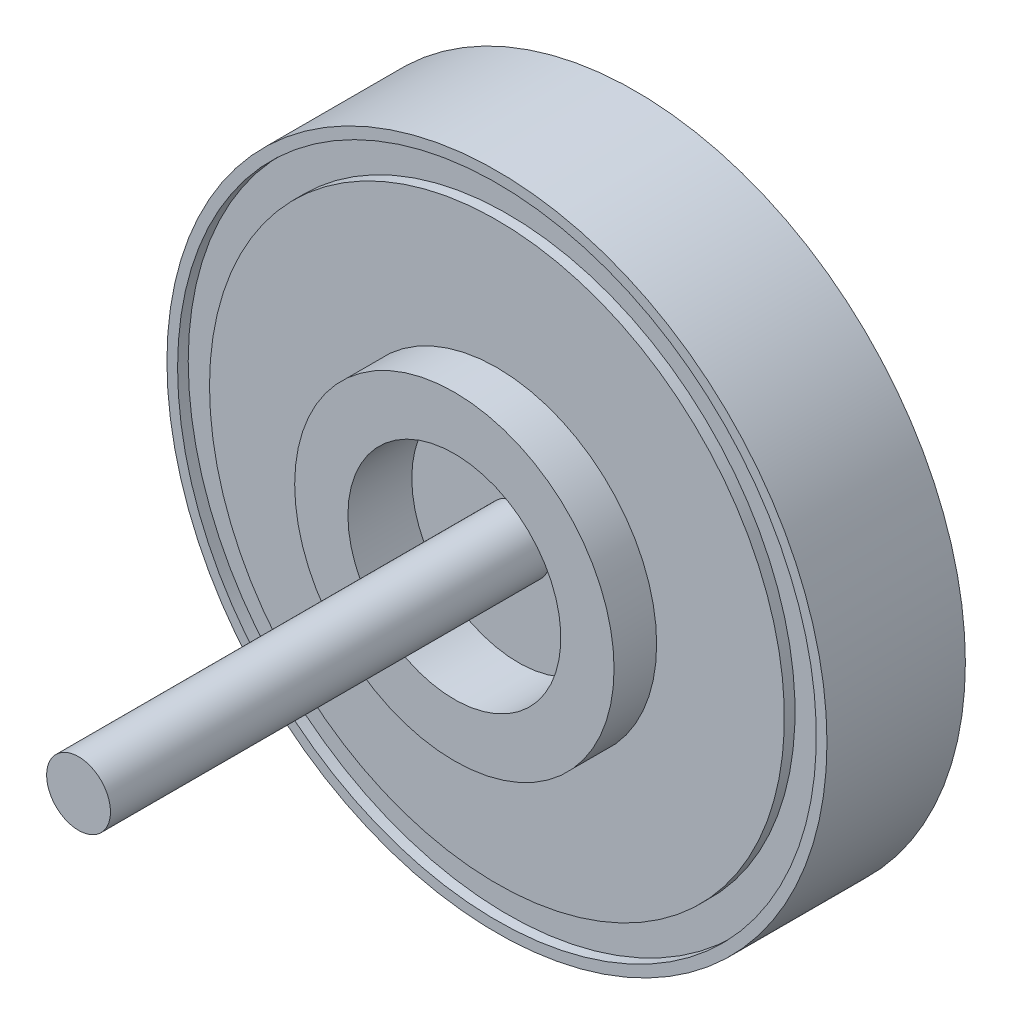
SolidWorks part; units mm, degrees
ref_plane "Alzado" through (0, 0, 0) normal (0, 0, 1) x (1, 0, 0)
ref_plane "Planta" through (0, 0, 0) normal (0, 1, 0) x (1, 0, 0)
ref_plane "Vista lateral" through (0, 0, 0) normal (1, 0, 0) x (0, 0, -1)
sketch "Croquis1" plane through (0, 0, 0) normal (1, 0, 0) x (0, 0, -1)
  line L0 (-41.3, 0) -> (-41.3, 3) construction
  line L1 (0, 10) -> (-6, 10) construction
  line L2 (-6, 10) -> (-6, 15) construction
  line L3 (-6, 15) -> (-2, 15) construction
  line L4 (-2, 15) -> (-2, 27) construction
  line L5 (-2, 27) -> (-1, 27) construction
  line L6 (-1, 27) -> (-1, 30) construction
  line L7 (-1, 30) -> (-2, 30) construction
  line L8 (-2, 30) -> (-2, 31) construction
  line L9 (-2, 31) -> (11, 31) construction
  line L10 (11, 31) -> (11, 29) construction
  line L11 (11, 29) -> (3, 29) construction
  line L12 (3, 29) -> (3, 22) construction
  line L13 (3, 22) -> (6, 22) construction
  line L14 (6, 22) -> (6, 14) construction
  line L15 (6, 14) -> (5, 14) construction
  line L16 (5, 14) -> (5, 9) construction
  line L17 (5, 9) -> (10, 9) construction
  line L18 (10, 9) -> (10, 3) construction
  line L19 (10, 3) -> (13.7, 3) construction
  line L20 (13.7, 3) -> (13.7, 0) construction
  line L21 (-41.3, 3) -> (0, 3) construction
  line L22 (0, 3) -> (0, 10) construction
  line L23 (-41.3, 0) -> (13.7, 0) construction
  line L24 (13.7, 0) -> (-41.3, 0)
  line L25 (-41.3, 0) -> (-41.3, 3)
  line L26 (-41.3, 3) -> (0, 3)
  line L27 (0, 3) -> (0, 10)
  line L28 (0, 10) -> (-6, 10)
  line L29 (-6, 10) -> (-6, 15)
  line L30 (-6, 15) -> (-2, 15)
  line L31 (-2, 15) -> (-2, 27)
  line L32 (-2, 27) -> (-1, 27)
  line L33 (-1, 27) -> (-1, 30)
  line L34 (-1, 30) -> (-2, 30)
  line L35 (-2, 30) -> (-2, 31)
  line L36 (-2, 31) -> (11, 31)
  line L37 (11, 31) -> (11, 29)
  line L38 (11, 29) -> (3, 29)
  line L39 (3, 29) -> (3, 22)
  line L40 (3, 22) -> (6, 22)
  line L41 (6, 22) -> (6, 14)
  line L42 (6, 14) -> (5, 14)
  line L43 (5, 14) -> (5, 9)
  line L44 (5, 9) -> (10, 9)
  line L45 (10, 9) -> (10, 3)
  line L46 (10, 3) -> (13.7, 3)
  line L47 (13.7, 3) -> (13.7, 0)
revolve "Revolución1" add sketch "Croquis1" angle 360 about L24
